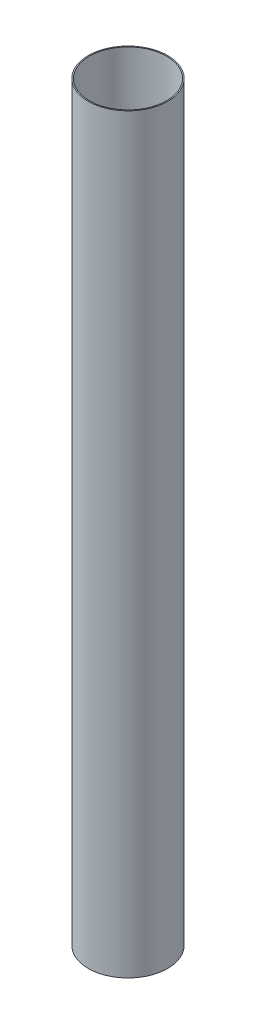
SolidWorks part; units mm, degrees
material "Thornel Mat VMA"
ref_plane "Front Plane" through (0, 0, 0) normal (0, 0, 1) x (1, 0, 0)
ref_plane "Top Plane" through (0, 0, 0) normal (0, 1, 0) x (1, 0, 0)
ref_plane "Right Plane" through (0, 0, 0) normal (1, 0, 0) x (0, 0, -1)
sketch "Sketch1" plane through (0, 0, 0) normal (0, 1, 0) x (1, 0, 0)
  circle A0 centre (0, 0) radius 46.1137
  circle A1 centre (0, 0) radius 44.8437
  dimension "D1" = 92.2274
  dimension "D2" = 1.27
extrude "Extrude1" add sketch "Sketch1" along normal blind 871.6667
